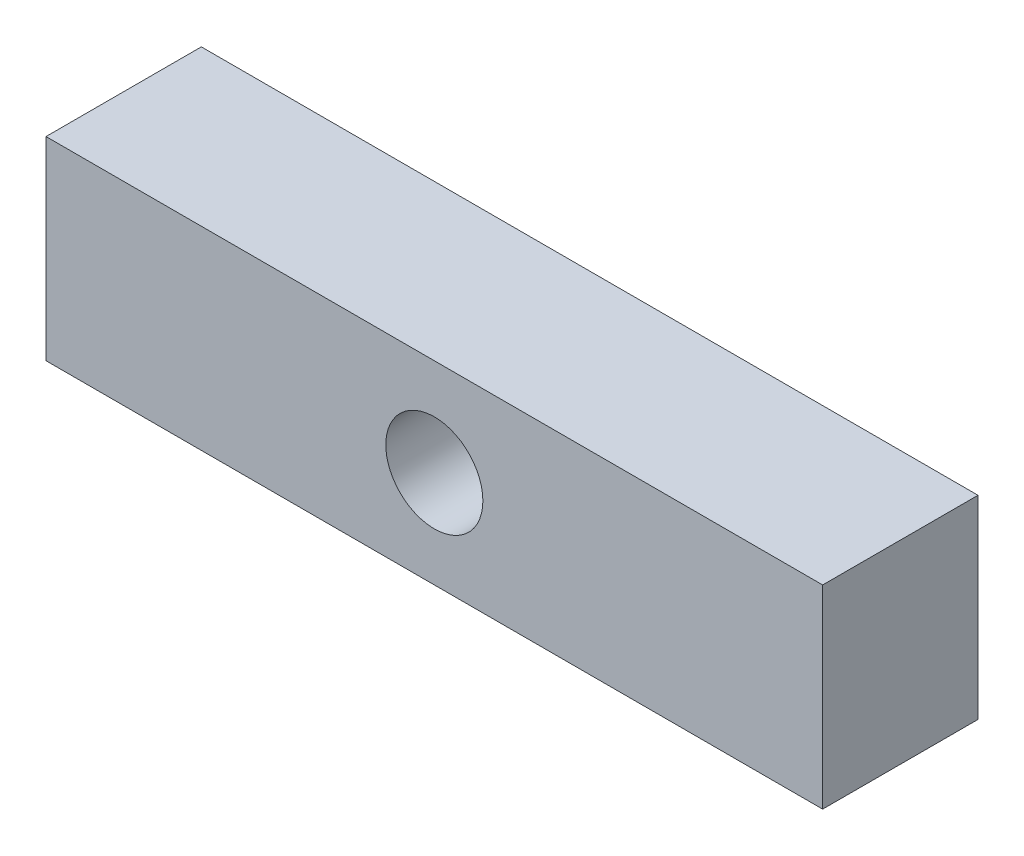
SolidWorks part; units mm, degrees
ref_plane "Front Plane" through (0, 0, 0) normal (0, 0, 1) x (1, 0, 0)
ref_plane "Top Plane" through (0, 0, 0) normal (0, 1, 0) x (1, 0, 0)
ref_plane "Right Plane" through (0, 0, 0) normal (1, 0, 0) x (0, 0, -1)
sketch "Sketch1" plane through (0, 0, 0) normal (0, 0, 1) x (1, 0, 0)
  line L1 (-20, 5) -> (20, 5)
  line L2 (-20, 5) -> (-20, -5)
  line L3 (-20, -5) -> (20, -5)
  line L4 (20, 5) -> (20, -5)
  line L5 (-20, 5) -> (20, -5) construction
  line L6 (-20, -5) -> (20, 5) construction
  circle A0 centre (0, 0) radius 2.5
  point P0 (0, 0)
  dimension "D3" = 5
  dimension "D1" = 40
  dimension "D2" = 10
extrude "Boss-Extrude1" add sketch "Sketch1" along normal blind 8
sketch "Sketch2" plane through (0, -5, 0) normal (0, -1, 0) x (-1, 0, 0)
  line L0 (-4, -8) -> (-4, 0) construction
  line L1 (20, -8) -> (-20, -8) construction
  line L2 (20, 0) -> (-20, 0) construction
  line L3 (-20, -8) -> (-20, 0) construction
  dimension "D1" = 16
